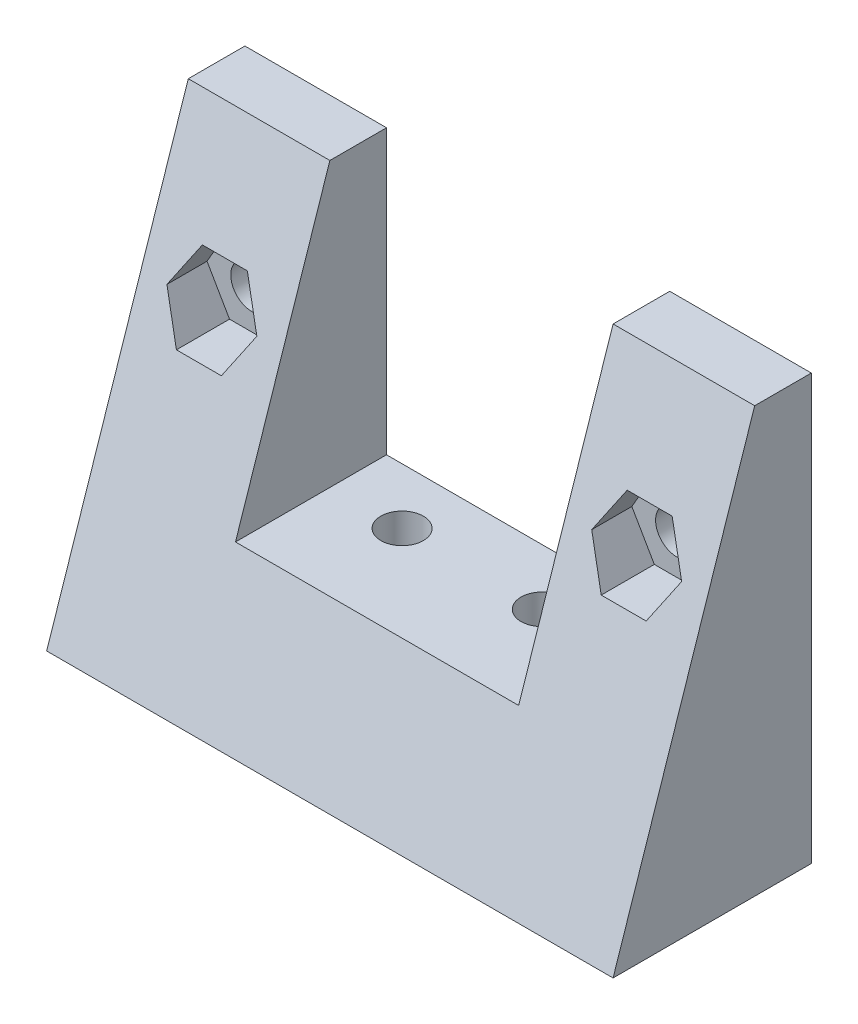
SolidWorks part; units mm, degrees
ref_plane "Спереди" through (0, 0, 0) normal (0, 0, 1) x (1, 0, 0)
ref_plane "Сверху" through (0, 0, 0) normal (0, 1, 0) x (1, 0, 0)
ref_plane "Справа" through (0, 0, 0) normal (1, 0, 0) x (0, 0, -1)
sketch "Sketch1" plane through (0, 0, 0) normal (1, 0, 0) x (0, 0, -1)
  line L0 (0, 0) -> (-14, 0)
  line L1 (-14, 0) -> (-4, 30)
  line L2 (-4, 30) -> (0, 30)
  line L3 (0, 30) -> (0, 0)
  dimension "D1" = 14
  dimension "D2" = 4
  dimension "D3" = 30
extrude "Extrude1" add sketch "Sketch1" against normal blind 40
sketch "Sketch2" plane through (0, 0, 0) normal (0, 0, -1) x (-1, 0, 0)
  line L0 (40, 30) -> (0, 30) construction
  line L1 (10, 30) -> (30, 30)
  line L2 (10, 30) -> (10, 10)
  line L3 (10, 10) -> (30, 10)
  line L4 (30, 30) -> (30, 10)
  line L5 (0, 0) -> (0, 30) construction
  line L6 (40, 0) -> (40, 30) construction
  line L7 (40, 0) -> (0, 0) construction
  dimension "D1" = 10
  dimension "D2" = 10
  dimension "D3" = 10
extrude "Extrude2" cut sketch "Sketch2" against normal through all
sketch "Sketch3" plane through (0, 0, 0) normal (0, 0, -1) x (-1, 0, 0)
  line L0 (10, 30) -> (10, 10) construction
  line L1 (10, 30) -> (0, 30) construction
  line L2 (20, 0) -> (20, 26.911) construction
  line L3 (40, 0) -> (0, 0) construction
  circle A0 centre (5, 20) radius 1.5
  circle A2 centre (35, 20) radius 1.5
  dimension "D1" = 3
  dimension "D2" = 5
  dimension "D3" = 10
extrude "Extrude3" cut sketch "Sketch3" against normal through all
sketch "Sketch4" plane through (0, 10, 0) normal (0, 1, 0) x (1, 0, 0)
  line L0 (-40, 0) -> (-30, 0) construction
  line L2 (-30, -10.6667) -> (-30, 0) construction
  line L3 (-20, -10.6667) -> (-20, 0) construction
  line L4 (-30, -10.6667) -> (-10, -10.6667) construction
  line L5 (-10, 0) -> (-30, 0) construction
  circle A0 centre (-24.95, -3.95) radius 1.5
  circle A1 centre (-15.05, -3.95) radius 1.5
  dimension "D1" = 3.95
  dimension "D2" = 3
  dimension "D3" = 5.05
extrude "Extrude4" cut sketch "Sketch4" against normal through all
ref_plane "Plane1" through (0, 0, 14) normal (0, 0, -1) x (-1, 0, 0)
sketch "Sketch8" plane through (0, 0, 14) normal (0, 0, -1) x (-1, 0, 0)
  line L0 (40, 0) -> (0, 0) construction
  line L1 (6.5877, 17.25) -> (8.1754, 20)
  line L2 (8.1754, 20) -> (6.5877, 22.75)
  line L3 (6.5877, 22.75) -> (3.4123, 22.75)
  line L4 (3.4123, 22.75) -> (1.8246, 20)
  line L5 (1.8246, 20) -> (3.4123, 17.25)
  line L6 (3.4123, 17.25) -> (6.5877, 17.25)
  line L7 (20, 0) -> (20, 29.8914) construction
  line L8 (40, 0) -> (0, 0) construction
  line L9 (36.5877, 17.25) -> (33.4123, 17.25)
  line L10 (38.1754, 20) -> (36.5877, 17.25)
  line L11 (36.5877, 22.75) -> (38.1754, 20)
  line L12 (33.4123, 22.75) -> (36.5877, 22.75)
  line L13 (31.8246, 20) -> (33.4123, 22.75)
  line L14 (33.4123, 17.25) -> (31.8246, 20)
  circle A0 centre (5, 20) radius 2.75 construction
  dimension "D1" = 5.5
extrude "Extrude5" cut sketch "Sketch8" along normal offset from surface (9.5 mm away) 4.5 up to face at (-5, 21.5, 0)
